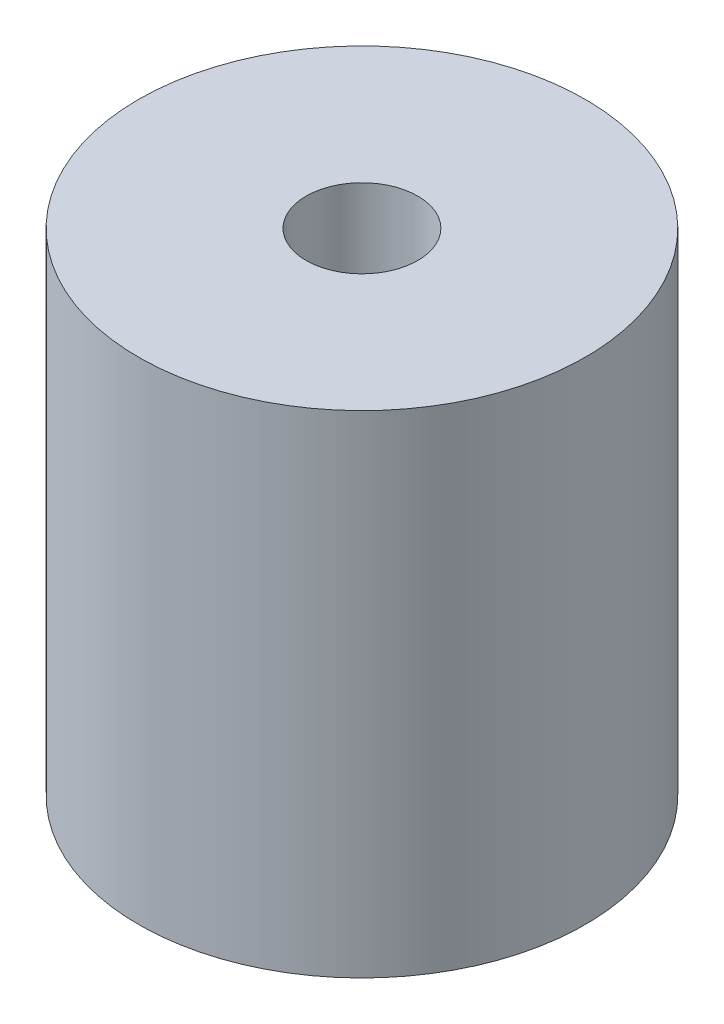
SolidWorks part; units mm, degrees
ref_plane "前视基准面" through (0, 0, 0) normal (0, 0, 1) x (1, 0, 0)
ref_plane "上视基准面" through (0, 0, 0) normal (0, 1, 0) x (1, 0, 0)
ref_plane "右视基准面" through (0, 0, 0) normal (1, 0, 0) x (0, 0, -1)
sketch "草图1" plane through (0, 0, 0) normal (0, 0, 1) x (1, 0, 0)
  line L0 (-13.1297, 20.6989) -> (-5.6297, 20.6989)
  line L1 (-5.6297, 20.6989) -> (-5.6297, 14.6989)
  line L2 (-5.6297, 14.6989) -> (-9.1297, 14.6989)
  line L3 (-9.1297, 14.6989) -> (-9.1297, -1.3011)
  line L4 (-9.1297, -1.3011) -> (-13.1297, -1.3011)
  line L5 (-13.1297, -1.3011) -> (-13.1297, 20.6989)
  line L6 (-3.1297, 20.6989) -> (-3.1297, -1.3011) construction
  point P8 (-3.1297, 20.6989)
  dimension "D1" = 2.5
  dimension "D2" = 10
  dimension "D3" = 6
  dimension "D4" = 10
  dimension "D5" = 22
  dimension "D6" = 6
revolve "旋转2" add sketch "草图1" angle 360 about L6
